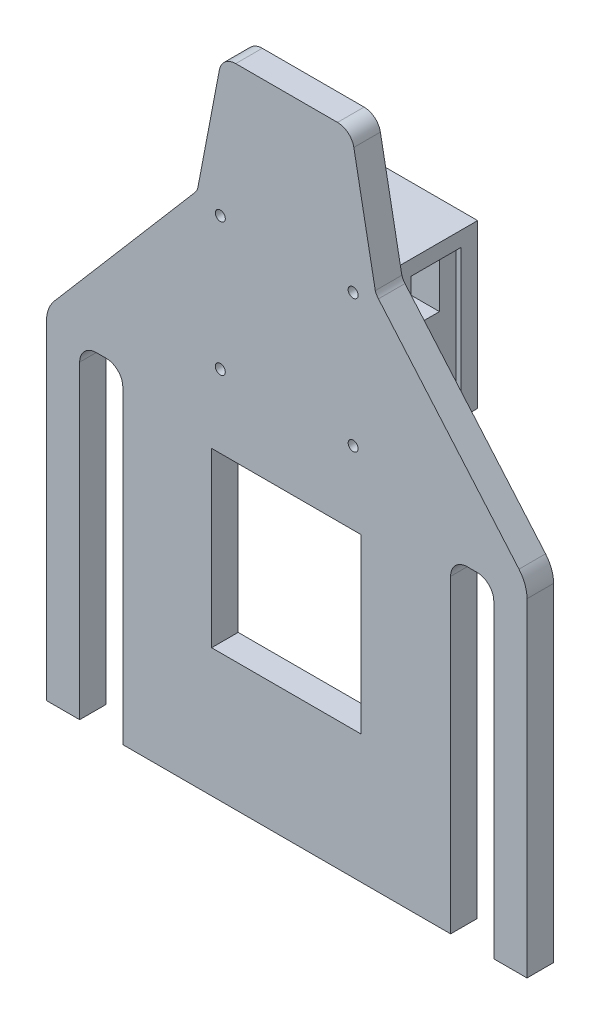
SolidWorks part; units mm, degrees
ref_plane "Front Plane" through (0, 0, 0) normal (0, 0, 1) x (1, 0, 0)
ref_plane "Top Plane" through (0, 0, 0) normal (0, 1, 0) x (1, 0, 0)
ref_plane "Right Plane" through (0, 0, 0) normal (1, 0, 0) x (0, 0, -1)
sketch "Sketch1" plane through (0, 0, 0) normal (0, 0, 1) x (1, 0, 0)
  line L4 (70, 309.9858) -> (85.2992, 309.9858)
  line L6 (43.2101, 271.7903) -> (49.7246, 305.9232)
  line L7 (42.2614, 270.1156) -> (0.0495, 220.7861)
  line L8 (0.0495, 220.7861) -> (42.9, 220.7861) construction
  line L9 (42.9, 220.7861) -> (42.9, 270.8599) construction
  line L10 (96.9829, 220.8599) -> (96.9829, 270.8599) construction
  line L11 (112.4871, 25.7747) -> (89.3829, 25.7747) construction
  line L12 (27.5129, 25.7747) -> (50.5, 25.7747) construction
  line L13 (25.2828, 25.7823) -> (2.6386, 25.8599)
  line L14 (96.6727, 271.7903) -> (90.212, 305.9159)
  line L15 (70, 329.5221) -> (70, -78.2612) construction
  line L18 (50.5, 25.7747) -> (50.5, 0) construction
  line L19 (70, 309.9858) -> (54.636, 309.9858)
  line L20 (135.9829, 220.8599) -> (96.9829, 220.8599) construction
  line L21 (139.9505, 220.7861) -> (135.9829, 220.8599) construction
  line L25 (89.3829, 25.7747) -> (89.3829, 0) construction
  line L27 (89.3829, 0) -> (50.5, 0)
  line L28 (7.6386, 35.4925) -> (20.6386, 35.4925)
  line L35 (127.3614, 35.4925) -> (124.3614, 35.4925)
  line L36 (124.3614, 213.626) -> (127.3614, 213.626)
  line L37 (119.3614, 40.4925) -> (119.3614, 208.626)
  line L38 (132.3614, 208.626) -> (132.3614, 40.4925)
  line L39 (142.3614, 214.274) -> (142.3614, 30.8599)
  line L40 (97.6215, 270.1156) -> (139.9505, 220.7861)
  line L41 (-2.3614, 214.274) -> (-2.3614, 30.8599)
  line L42 (7.6386, 208.626) -> (7.6386, 35.4925)
  line L43 (20.6386, 35.4925) -> (20.6386, 208.626)
  line L44 (15.6386, 213.626) -> (12.6386, 213.626)
  line L45 (28.9972, 24.1103) -> (50.5, 0)
  line L46 (114.7172, 25.7823) -> (137.3614, 25.8599)
  line L47 (89.3829, 0) -> (111.0028, 24.1103)
  arc A1 (42.2614, 270.1156) -> (43.2101, 271.7903) centre (38.4667, 273.3715) ccw
  arc A5 (97.6215, 270.1156) -> (96.6727, 271.7903) centre (101.4161, 273.3715) cw
  arc A8 (137.3614, 25.8599) -> (142.3614, 30.8599) centre (137.3614, 30.8599) ccw
  arc A9 (2.6386, 25.8599) -> (-2.3614, 30.8599) centre (2.6386, 30.8599) cw
  arc A10 (49.7246, 305.9232) -> (54.636, 309.9858) centre (54.636, 304.9858) cw
  arc A11 (85.2992, 309.9858) -> (90.212, 305.9159) centre (85.2992, 304.9858) cw
  arc A12 (139.9505, 220.7861) -> (142.3614, 214.274) centre (132.3614, 214.274) cw
  arc A13 (0.0495, 220.7861) -> (-2.3614, 214.274) centre (7.6386, 214.274) ccw
  arc A14 (25.2828, 25.7823) -> (28.9972, 24.1103) centre (25.2657, 20.7823) cw
  arc A15 (114.7172, 25.7823) -> (111.0028, 24.1103) centre (114.7343, 20.7823) ccw
  arc A16 (15.6386, 213.626) -> (20.6386, 208.626) centre (15.6386, 208.626) cw
  arc A17 (7.6386, 208.626) -> (12.6386, 213.626) centre (12.6386, 208.626) cw
  arc A18 (127.3614, 35.4925) -> (132.3614, 40.4925) centre (127.3614, 40.4925) ccw
  arc A19 (124.3614, 35.4925) -> (119.3614, 40.4925) centre (124.3614, 40.4925) cw
  arc A20 (127.3614, 213.626) -> (132.3614, 208.626) centre (127.3614, 208.626) cw
  arc A21 (119.3614, 208.626) -> (124.3614, 213.626) centre (124.3614, 208.626) cw
  point P18 (20.6386, 213.626)
  point P51 (7.6386, 213.626)
  point P57 (132.3614, 35.4925)
  point P61 (119.3614, 35.4925)
  point P67 (132.3614, 213.626)
  point P70 (119.3614, 213.626)
  dimension "D1" = 5
  dimension "D2" = 5
  dimension "D3" = 5
  dimension "D4" = 10
  dimension "D5" = 5
  dimension "D6" = 5
extrude "Boss-Extrude1" add sketch "Sketch1" along normal blind 8
sketch "Sketch2" plane through (0, 0, 8) normal (0, 0, 1) x (1, 0, 0)
  line L2 (92.3829, 206.0089) -> (47.3829, 206.0089)
  line L8 (47.3829, 206.0089) -> (47.3829, 154.0089)
  line L9 (47.3829, 154.0089) -> (92.3829, 154.0089)
  line L10 (92.3829, 206.0089) -> (92.3829, 154.0089)
extrude "Cut-Extrude1" cut sketch "Sketch2" against normal through all contours L10 L2 L8 L9
sketch "Sketch3" plane through (0, 0, 0) normal (0, 0, -1) x (-1, 0, 0)
  line L1 (-142.3614, 115.3599) -> (2.3614, 115.3599)
  line L3 (-142.3614, 30.8599) -> (-142.3614, 214.274) construction
  line L6 (2.3614, 214.274) -> (2.3614, 30.8599) construction
split "Split1" trim tools "Sketch3" bodies to split 102 resulting bodies 104 108
ref_plane "Plane4" through (0, 115.3599, 0) normal (0, 1, 0) x (1, 0, 0)
sketch "Sketch4" plane through (0, 115.3599, 0) normal (0, -1, 0) x (-1, 0, 0)
  line L0 (-2.6386, -8) -> (-2.6386, -4)
  line L2 (2.3614, -8) -> (-7.6386, -8) construction
  circle A1 centre (-70, -4) radius 2.5
  circle A2 centre (-40, -4) radius 2.5
  circle A3 centre (-100, -4) radius 2.5
  circle A5 centre (-137.3614, -4) radius 2.5
  circle A6 centre (-2.6386, -4) radius 2.5
sketch "Sketch5" plane through (0, 115.3599, -115.3599) normal (0, -1, 0) x (1, 0, 0)
  circle A1 centre (70, 119.3599) radius 2.5
  circle A2 centre (100, 119.3599) radius 2.5
  circle A3 centre (40, 119.3599) radius 2.5
  circle A5 centre (2.6386, 119.3599) radius 2.5
  circle A6 centre (137.3614, 119.3599) radius 2.5
extrude "Cut-Extrude6" cut sketch "Sketch5" along direction (0, -1, 0) on the side of the normal blind 5.2 contours A5 | A3 | A1
extrude "Cut-Extrude7" cut sketch "Sketch4" against normal blind 5.2
delete or keep bodies "Body-Delete/Keep 3" type delete bodies bodies 106
sketch "Sketch6" plane through (0, 0, 8) normal (0, 0, 1) x (1, 0, 0)
  circle A0 centre (50.0001, 267.9803) radius 1.5
  circle A1 centre (90.0001, 267.9803) radius 1.5
  circle A2 centre (90.0001, 227.9803) radius 1.5
  circle A3 centre (50.0001, 227.9803) radius 1.5
extrude "Cut-Extrude8" cut sketch "Sketch6" against normal through all
sketch "Sketch7" plane through (0, 0, 0) normal (0, 0, -1) x (-1, 0, 0)
  line L10 (-94.5001, 223.4803) -> (-94.5001, 272.4803)
  line L11 (-47.0001, 270.9803) -> (-47.0001, 252.9803)
  line L12 (-45.5001, 272.4803) -> (-45.5001, 223.4803)
  line L13 (-45.5001, 223.4803) -> (-94.5001, 223.4803)
  line L14 (-93.0001, 270.9803) -> (-75.0001, 270.9803)
  line L15 (-93.0001, 224.9803) -> (-75.0001, 224.9803)
  line L16 (-93.0001, 224.9803) -> (-93.0001, 242.9803)
  line L18 (-65.0001, 270.9803) -> (-65.0001, 252.9803)
  line L19 (-65.0001, 224.9803) -> (-47.0001, 224.9803)
  line L20 (-45.5001, 272.4803) -> (-94.5001, 272.4803)
  line L21 (-75.0001, 270.9803) -> (-75.0001, 252.9803)
  line L22 (-47.0001, 252.9803) -> (-65.0001, 252.9803)
  line L23 (-47.0001, 242.9803) -> (-47.0001, 224.9803)
  line L24 (-93.0001, 242.9803) -> (-75.0001, 242.9803)
  line L25 (-65.0001, 270.9803) -> (-47.0001, 270.9803)
  line L26 (-75.0001, 252.9803) -> (-93.0001, 252.9803)
  line L27 (-65.0001, 242.9803) -> (-47.0001, 242.9803)
  line L28 (-65.0001, 242.9803) -> (-65.0001, 224.9803)
  line L29 (-75.0001, 242.9803) -> (-75.0001, 224.9803)
  line L30 (-93.0001, 252.9803) -> (-93.0001, 270.9803)
extrude "Boss-Extrude2" add sketch "Sketch7" along normal blind 15
sketch "Sketch8" plane through (0, 0, -15) normal (0, 0, -1) x (-1, 0, 0)
  line L0 (-45.5001, 272.4803) -> (-94.5001, 272.4803)
  line L1 (-94.5001, 272.4803) -> (-94.5001, 223.4803)
  line L2 (-94.5001, 223.4803) -> (-45.5001, 223.4803)
  line L3 (-94.5001, 223.4803) -> (-45.5001, 223.4803) construction
  line L4 (-94.5001, 223.4803) -> (-45.5001, 223.4803) construction
  line L5 (-45.5001, 223.4803) -> (-45.5001, 272.4803)
  circle A0 centre (-50.0001, 267.9803) radius 1.5
  circle A1 centre (-90.0001, 267.9803) radius 1.5
  circle A2 centre (-50.0001, 227.9803) radius 1.5
  circle A3 centre (-90.0001, 227.9803) radius 1.5
extrude "Boss-Extrude3" add sketch "Sketch8" along normal blind 10
sketch "Sketch9" plane through (45.5001, 0, 0) normal (-1, 0, 0) x (0, 0, 1)
  line L2 (-20, 267.9803) -> (-20, 227.9803)
  line L3 (-20, 267.9803) -> (-5, 267.9803)
  line L6 (-5, 267.9803) -> (-5, 227.9803)
  line L7 (-5, 227.9803) -> (-20, 227.9803)
extrude "Cut-Extrude9" cut sketch "Sketch9" against normal blind 1.5
sketch "Sketch11" plane through (94.5001, 0, 0) normal (1, 0, 0) x (0, 0, -1)
  line L3 (20, 267.9803) -> (20, 227.9803)
  line L4 (20, 227.9803) -> (5, 227.9803)
  line L5 (5, 227.9803) -> (5, 267.9803)
  line L6 (5, 267.9803) -> (20, 267.9803)
extrude "Cut-Extrude10" cut sketch "Sketch11" against normal blind 1.5
